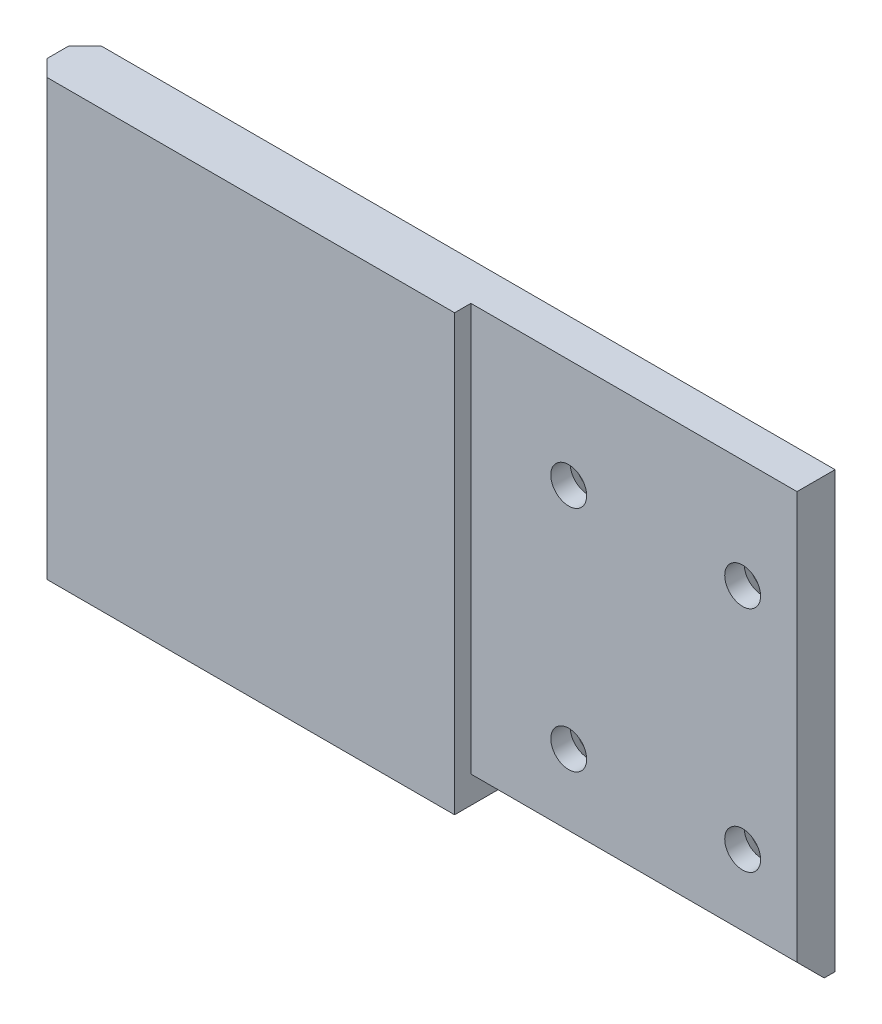
SolidWorks part; units mm, degrees
material "AISI 1045 Aço, trefilado"
ref_plane "Plano frontal" through (0, 0, 0) normal (0, 0, 1) x (1, 0, 0)
ref_plane "Plano superior" through (0, 0, 0) normal (0, 1, 0) x (1, 0, 0)
ref_plane "Plano direito" through (0, 0, 0) normal (1, 0, 0) x (0, 0, -1)
sketch "Esboço1" plane through (0, 0, 0) normal (0, 0, 1) x (1, 0, 0)
  line L1 (0, 0) -> (-138, 0)
  line L2 (0, 0) -> (0, 80)
  line L3 (0, 80) -> (-138, 80)
  line L4 (-138, 0) -> (-138, 80)
  dimension "D1" = 138
  dimension "D2" = 80
extrude "Ressalto-extrusão1" add sketch "Esboço1" along normal blind 10
sketch "Esboço2" plane through (0, 0, 10) normal (0, 0, 1) x (1, 0, 0)
  line L0 (0, 80) -> (-138, 80) construction
  line L1 (0, 0) -> (-60, 0)
  line L2 (0, 0) -> (0, 80)
  line L3 (0, 80) -> (-60, 80)
  line L4 (-60, 0) -> (-60, 80)
  dimension "D1" = 60
extrude "Corte-extrusão1" cut sketch "Esboço2" against normal blind 3
hole_wizard "Escareado para parafuso Allen sextavado escareado de M62" positions "Esboço5" profile "Esboço6" countersink size "M6" standard "ISO" end condition through all
sketch "Esboço5" plane through (0, 0, 0) normal (0, 0, -1) x (-1, 0, 0)
  line L1 (138, 0) -> (0, 0) construction
  line L5 (0, 0) -> (0, 80) construction
  point P0 (10, 60)
  point P2 (42, 60)
  point P4 (42, 18)
  point P6 (10, 18)
  point P17 (0, 0)
  point P22 (0, 0)
  dimension "D1" = 18
  dimension "D2" = 20
  dimension "D3" = 42
  dimension "D4" = 42
  dimension "D5" = 18
  dimension "D6" = 10
  dimension "D7" = 32
sketch "Esboço6" plane through (-10, 60, 0) normal (1, 0, 0) x (0, 1, 0)
  line L0 (0, 0) -> (0, 10)
  line L1 (0, 10) -> (3.3, 10)
  line L2 (3.3, 10) -> (3.3, 3.42)
  line L3 (3.3, 3.42) -> (6.72, 0)
  line L5 (6.72, 0) -> (0, 0)
  line L6 (-3.3, 3.42) -> (-6.72, 0) construction
  line L11 (0, -6.35) -> (0, 107.95) construction
  dimension "Thru Hole Dia." = 6.6
  dimension "Thru Hole Depth" = 10
  dimension "Near C'Sink Dia." = 13.44
  dimension "Near C'Sink Angle" = 90
chamfer "Chanfro1" distance 5 angle 45 1 edges at (-30, 0, 7)
chamfer "Chanfro2" distance 3 angle 45 2 edges at (-138, 40, 0) (-138, 40, 10)
